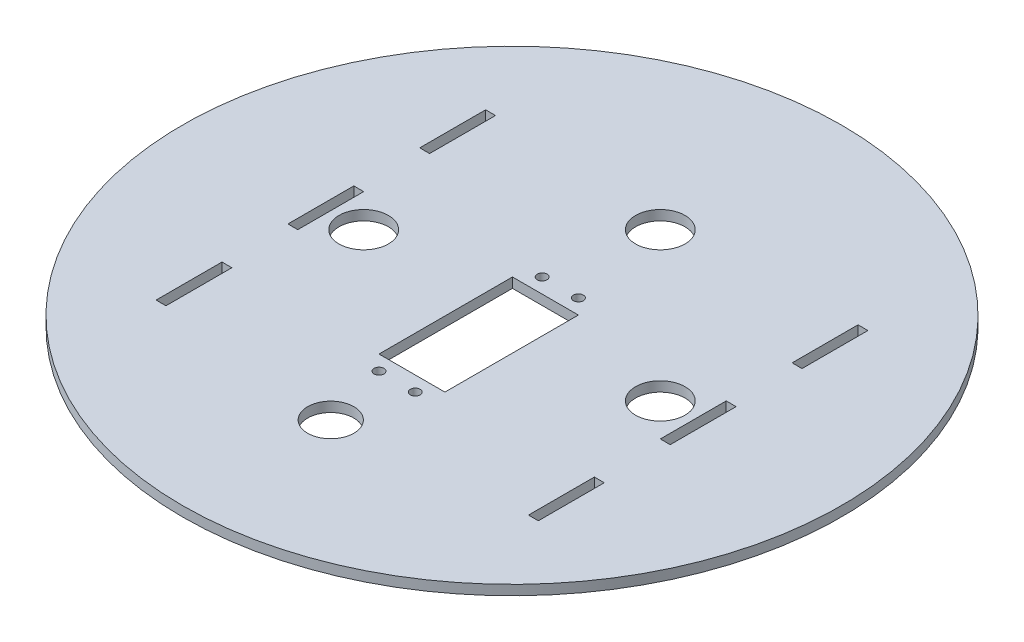
SolidWorks part; units mm, degrees
ref_plane "Alzado" through (0, 0, 0) normal (0, 0, 1) x (1, 0, 0)
ref_plane "Planta" through (0, 0, 0) normal (0, 1, 0) x (1, 0, 0)
ref_plane "Vista lateral" through (0, 0, 0) normal (1, 0, 0) x (0, 0, -1)
sketch "Sketch2" plane through (0, 0, 0) normal (0, 1, 0) x (1, 0, 0)
  circle A0 centre (0, 0) radius 100
extrude "Boss-Extrude1" add sketch "Sketch2" along normal mid plane 3
sketch "Sketch3" plane through (0, -1.5, 0) normal (0, -1, 0) x (1, 0, 0)
  line L0 (-55, 0) -> (55, 0)
  line L1 (0, 0) -> (0, -66.1396) construction
  line L2 (-58, 0) -> (-58, -10)
  line L3 (-58, -50) -> (-55, -50)
  line L4 (-55, -50) -> (-55, -30)
  line L5 (-55, 50) -> (-58, 50)
  line L6 (-58, 50) -> (-58, 30)
  line L12 (-58, -50) -> (-58, -30)
  line L13 (58, 30) -> (58, 50)
  line L14 (-58, -10) -> (-58, 10)
  line L15 (58, -10) -> (58, 10)
  line L16 (-58, 30) -> (-58, 50)
  line L17 (-58, -30) -> (-55, -30)
  line L18 (-58, -10) -> (-55, -10)
  line L19 (-58, 10) -> (-55, 10)
  line L20 (-58, 30) -> (-55, 30)
  line L21 (-55, 30) -> (-55, 50)
  line L22 (-58, 10) -> (-58, 0)
  line L23 (-55, -10) -> (-55, 10)
  line L24 (-58, -30) -> (-58, -50)
  line L25 (58, -50) -> (58, -30)
  line L26 (58, -30) -> (58, -50)
  line L27 (55, -10) -> (55, 10)
  line L28 (58, 10) -> (58, 0)
  line L29 (55, 30) -> (55, 50)
  line L30 (58, 30) -> (55, 30)
  line L31 (58, 10) -> (55, 10)
  line L32 (58, -10) -> (55, -10)
  line L33 (58, -30) -> (55, -30)
  line L34 (58, 50) -> (58, 30)
  line L35 (55, 50) -> (58, 50)
  line L36 (55, -50) -> (55, -30)
  line L37 (58, -50) -> (55, -50)
  line L38 (58, 0) -> (58, -10)
  dimension "D1" = 50
  dimension "D4" = 55
  dimension "D2" = 3
  dimension "D3" = 100
  dimension "D5" = 20
  dimension "D6" = 20
  dimension "D7" = 20
  dimension "D8" = 20
sketch "Sketch5" plane through (0, -1.5, 0) normal (0, -1, 0) x (1, 0, 0)
  line L0 (0, 0) -> (0, 30.36) construction
  line L1 (0, 30.36) -> (10, 30.36)
  line L2 (10, 30.36) -> (10, -10.14)
  line L3 (10, -10.14) -> (-10, -10.14)
  line L4 (-10, -10.14) -> (-10, 30.36)
  line L5 (-10, 30.36) -> (0, 30.36)
  dimension "D1" = 30.36
  dimension "D2" = 10
  dimension "D3" = 40.5
  dimension "D4" = 20
extrude "Cut-Extrude2" cut sketch "Sketch5" against normal blind 10
sketch "Sketch6" plane through (0, -1.5, 0) normal (0, -1, 0) x (1, 0, 0)
  line L0 (0, 0) -> (0, -45) construction
  line L1 (0, 0) -> (0, 55) construction
  line L2 (0, 0) -> (45, 0) construction
  line L3 (0, 0) -> (-45, 0) construction
  circle A0 centre (-45, 0) radius 7.5
  circle A1 centre (0, -45) radius 7.5
  circle A2 centre (45, 0) radius 7.5
  circle A3 centre (0, 55) radius 7
  dimension "D3" = 45
  dimension "D1" = 55
  dimension "D2" = 45
extrude "Cut-Extrude3" cut sketch "Sketch6" against normal blind 10
extrude "Cut-Extrude4" cut sketch "Sketch3" against normal blind 10 contours L20 L21 L5 L6 | L18 L23 L19 L14 L2 | L17 L12 L3 L4 | L35 L29 L30 L13 | L32 L15 L31 L27 | L37 L25 L33 L36
sketch "Sketch7" plane through (0, -1.5, 0) normal (0, -1, 0) x (-1, 0, 0)
  line L0 (0, -30.36) -> (0, -36.36) construction
  line L1 (-10, -30.36) -> (10, -30.36) construction
  line L2 (5.5, -36.36) -> (5.5, -34.86) construction
  line L3 (0, -36.36) -> (7, -36.36) construction
  line L4 (7, -36.36) -> (5.5, -36.36) construction
  line L5 (-10, -30.36) -> (-10, 10.14) construction
  line L6 (-10, 10.14) -> (-10, -10.11) construction
  line L7 (-10, -10.11) -> (10, -10.11) construction
  line L8 (10, -30.36) -> (10, 10.14) construction
  line L9 (5.5, 16.14) -> (5.5, 14.64) construction
  line L10 (0, 10.14) -> (0, 16.14) construction
  circle A1 centre (5.5, -34.86) radius 1.5
  circle A2 centre (-5.5, -34.86) radius 1.5
  circle A3 centre (-5.5, 14.64) radius 1.5
  circle A4 centre (5.5, 14.64) radius 1.5
  point P26 (0, 0)
  dimension "D1" = 6
  dimension "D2" = 1.5
  dimension "D3" = 7
  dimension "D4" = 1.5
extrude "Cut-Extrude5" cut sketch "Sketch7" against normal blind 10 contours A1 | A2 | A3 | A4
